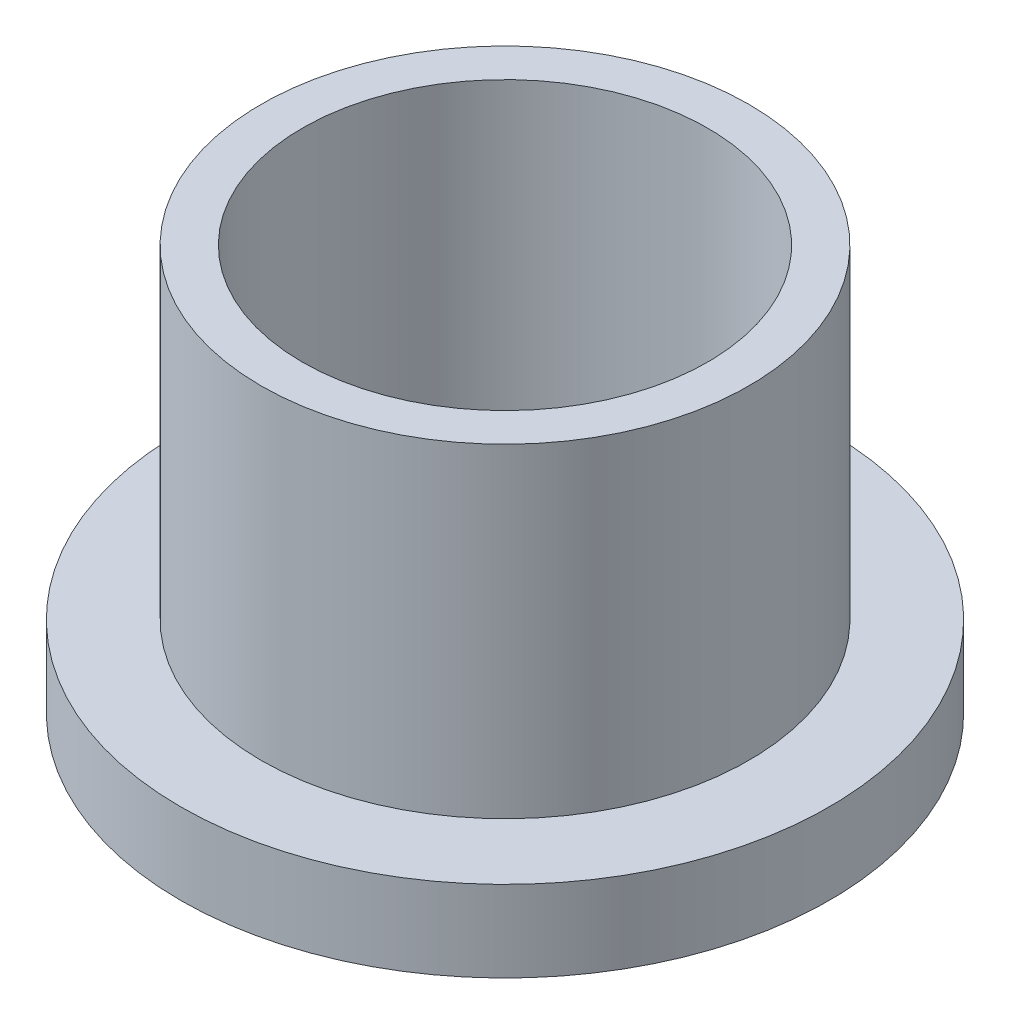
SolidWorks part; units mm, degrees
ref_plane "Front" through (0, 0, 0) normal (0, 0, 1) x (1, 0, 0)
ref_plane "Top" through (0, 0, 0) normal (0, 1, 0) x (1, 0, 0)
ref_plane "Right" through (0, 0, 0) normal (1, 0, 0) x (0, 0, -1)
sketch "Sketch1" plane through (0, 0, 0) normal (0, 1, 0) x (1, 0, 0)
  circle A0 centre (0, 0) radius 7.9375
  circle A1 centre (0, 0) radius 9.5504
  circle A2 centre (0, 0) radius 12.7
  dimension "ID" = 15.875
  dimension "OD" = 19.1008
  dimension "FlangeOD" = 25.4
sketch "Sketch2" plane through (0, 0, 0) normal (0, 1, 0) x (1, 0, 0)
  circle A0 centre (0, 0) radius 7.9375 construction
  circle A1 centre (0, 0) radius 9.5504 construction
  circle A2 centre (0, 0) radius 7.9375
  circle A3 centre (0, 0) radius 9.5504
extrude "Boss-Extrude1" add sketch "Sketch2" along normal blind 15.875
sketch "Sketch3" plane through (0, 0, 0) normal (0, 1, 0) x (1, 0, 0)
  circle A0 centre (0, 0) radius 12.7 construction
  circle A1 centre (0, 0) radius 9.5504 construction
  circle A2 centre (0, 0) radius 12.7
  circle A3 centre (0, 0) radius 9.5504
extrude "Boss-Extrude2" add sketch "Sketch3" along normal blind 3.175
